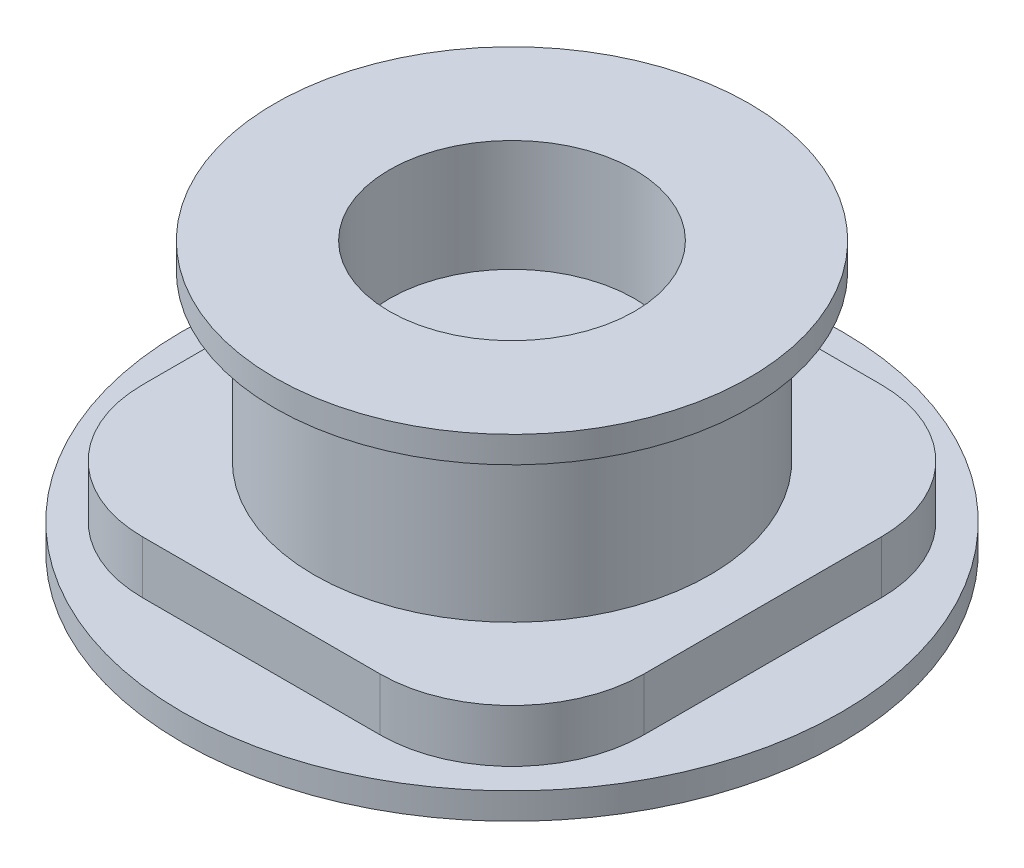
SolidWorks part; units mm, degrees
ref_plane "前视基准面" through (0, 0, 0) normal (0, 0, 1) x (1, 0, 0)
ref_plane "上视基准面" through (0, 0, 0) normal (0, 1, 0) x (1, 0, 0)
ref_plane "右视基准面" through (0, 0, 0) normal (1, 0, 0) x (0, 0, -1)
other "Configuration Table"
sketch "草图3" plane through (0, 0, 0) normal (0, 1, 0) x (1, 0, 0)
  line L1 (-95, 95) -> (95, 95)
  line L2 (-95, 95) -> (-95, -95)
  line L3 (-95, -95) -> (95, -95)
  line L4 (95, 95) -> (95, -95)
  line L5 (-95, 95) -> (95, -95) construction
  line L6 (-95, -95) -> (95, 95) construction
  point P0 (0, 0)
  dimension "D1" = 190
  dimension "D2" = 190
extrude "凸台-拉伸3" add sketch "草图3" along normal blind 20
fillet "圆角2" radius 50 4 edges at (95, 10, 95) (-95, 10, 95) (95, 10, -95) (-95, 10, -95)
sketch "草图4" plane through (0, 20, 0) normal (0, 1, 0) x (1, 0, 0)
  circle A0 centre (0, 0) radius 75
  dimension "D1" = 150
extrude "凸台-拉伸4" add sketch "草图4" along normal blind 42.3
sketch "草图5" plane through (0, 62.3, 0) normal (0, 1, 0) x (1, 0, 0)
  circle A0 centre (0, 0) radius 75
  dimension "D1" = 150
extrude "凸台-拉伸5" add sketch "草图5" along normal blind 20
sketch "草图12" plane through (0, 82.3, 0) normal (0, 1, 0) x (1, 0, 0)
  circle A0 centre (0, 0) radius 54
  dimension "D1" = 108
sketch "草图14" plane through (0, 82.3, 0) normal (0, 1, 0) x (1, 0, 0)
  circle A0 centre (0, 0) radius 90
  dimension "D1" = 180
extrude "凸台-拉伸7" add sketch "草图14" along normal blind 10
sketch "草图15" plane through (0, 92.3, 0) normal (0, 1, 0) x (1, 0, 0)
  circle A0 centre (0, 0) radius 46.5
  dimension "D1" = 93
extrude "切除-拉伸9" cut sketch "草图15" against normal blind 42.3
extrude "凸台-拉伸6" add sketch "草图12" along normal blind 10
sketch "草图13" plane through (0, 92.3, 0) normal (0, 1, 0) x (1, 0, 0)
  circle A0 centre (0, 0) radius 46.5
  dimension "D1" = 93
extrude "切除-拉伸7" cut sketch "草图13" against normal blind 41.3 contours A0
sketch "草图18" plane through (0, 0, 0) normal (0, -1, 0) x (1, 0, 0)
  circle A0 centre (0, 0) radius 125
  dimension "D1" = 250
extrude "凸台-拉伸8" add sketch "草图18" along normal blind 10
